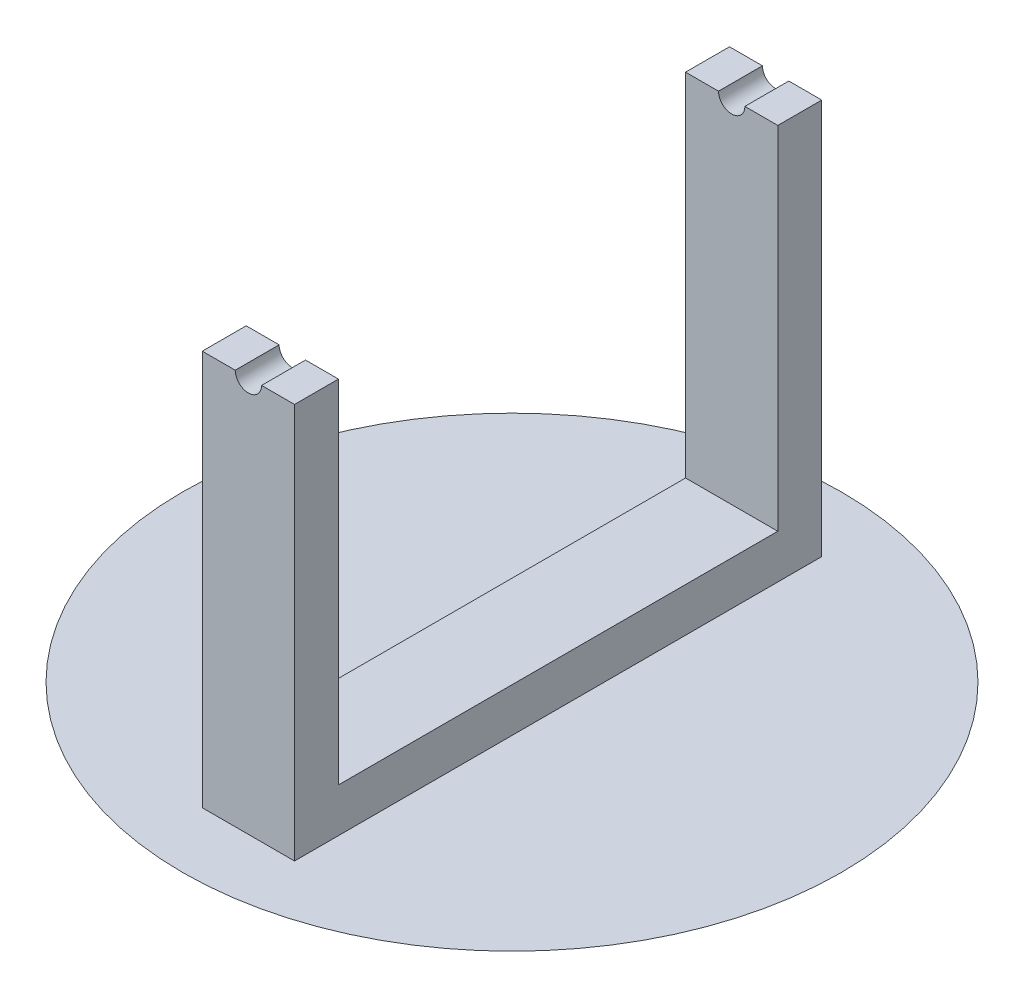
SolidWorks part; units mm, degrees
ref_plane "Front Plane" through (0, 0, 0) normal (0, 0, 1) x (1, 0, 0)
ref_plane "Top Plane" through (0, 0, 0) normal (0, 1, 0) x (1, 0, 0)
ref_plane "Right Plane" through (0, 0, 0) normal (1, 0, 0) x (0, 0, -1)
sketch "Sketch1" plane through (0, 0, 0) normal (1, 0, 0) x (0, 0, -1)
  line L0 (-120, 0) -> (-100, 0)
  line L1 (-100, 0) -> (-100, -160)
  line L2 (-100, -160) -> (100, -160)
  line L3 (100, -160) -> (100, 0)
  line L4 (100, 0) -> (120, 0)
  line L5 (120, 0) -> (120, -180)
  line L6 (120, -180) -> (-120, -180)
  line L7 (-120, -180) -> (-120, 0)
  point P9 (0, -160)
  point P10 (0, -180)
  dimension "D1" = 20
  dimension "D2" = 200
  dimension "D3" = 160
  dimension "D4" = 20
extrude "Boss-Extrude1" add sketch "Sketch1" along normal mid plane 42
sketch "Sketch2" plane through (0, 0, 0) normal (0, 0, 1) x (1, 0, 0)
  line L0 (150, -180) -> (79.9546, -220)
  line L1 (79.9546, -220) -> (0, -220)
  line L2 (0, -220) -> (0, -180)
  line L3 (0, -180) -> (150, -180)
  line L4 (21, -180) -> (-21, -180) construction
  line L5 (21, -180) -> (-21, -180)
  line L6 (0, 87.7264) -> (0, -269.6144) construction
  circle A0 centre (0, 0) radius 245 construction
  point P11 (79.9546, -220)
  dimension "D2" = 490
  dimension "D1" = 300
  dimension "D3" = 40
revolve "Revolve1" add sketch "Sketch2" angle 360 about L6
sketch "Sketch3" plane through (0, 0, 0) normal (0, 0, 1) x (1, 0, 0)
  circle A0 centre (0, 0) radius 6
  dimension "D1" = 12
extrude "Cut-Extrude1" cut sketch "Sketch3" against normal through all both and the other way through all
